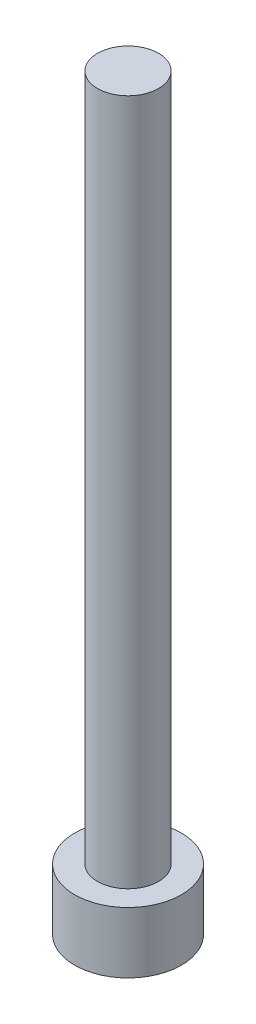
SolidWorks part; units mm, degrees
ref_plane "前视基准面" through (0, 0, 0) normal (0, 0, 1) x (1, 0, 0)
ref_plane "上视基准面" through (0, 0, 0) normal (0, 1, 0) x (1, 0, 0)
ref_plane "右视基准面" through (0, 0, 0) normal (1, 0, 0) x (0, 0, -1)
sketch "草图1" plane through (0, 0, 0) normal (0, 1, 0) x (1, 0, 0)
  circle A0 centre (0, 0) radius 2
extrude "凸台-拉伸1" add sketch "草图1" along normal blind 45
sketch "草图2" plane through (0, 0, 0) normal (0, -1, 0) x (1, 0, 0)
  circle A0 centre (0, 0) radius 3.5
extrude "凸台-拉伸2" add sketch "草图2" along normal blind 4
